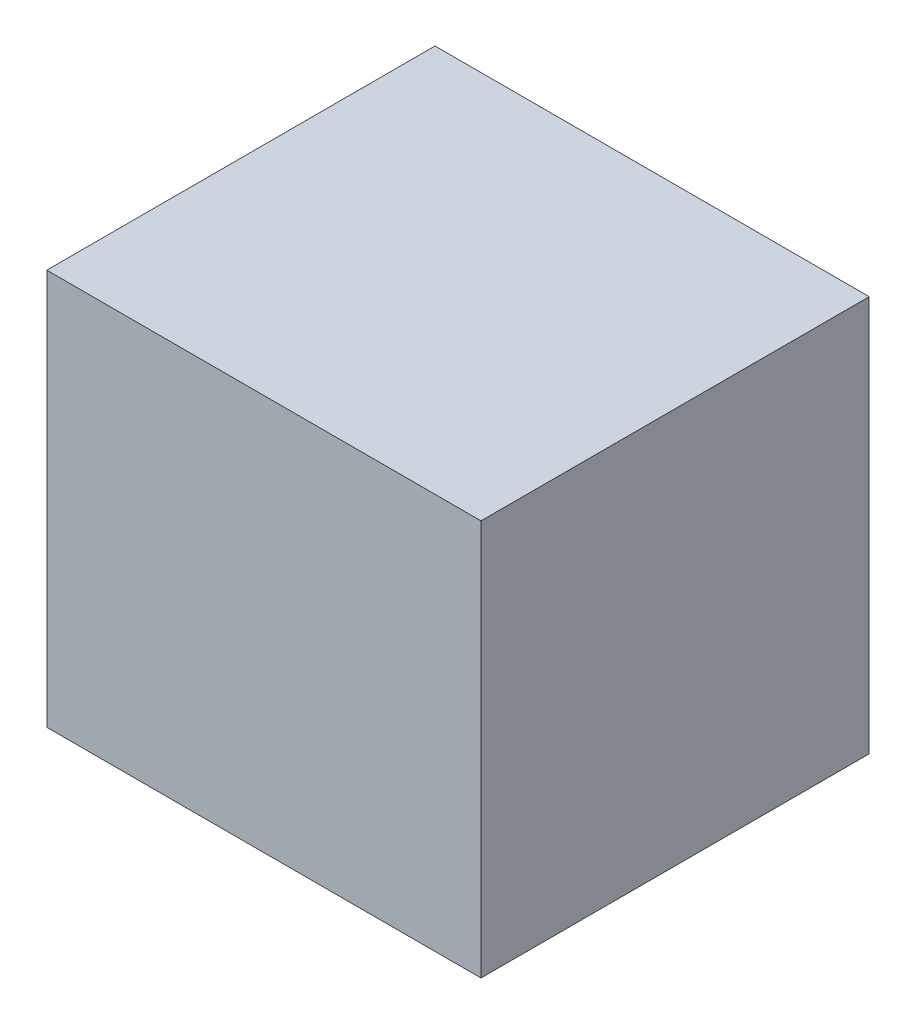
SolidWorks part; units mm, degrees
ref_plane "정면" through (0, 0, 0) normal (0, 0, 1) x (1, 0, 0)
ref_plane "윗면" through (0, 0, 0) normal (0, 1, 0) x (1, 0, 0)
ref_plane "우측면" through (0, 0, 0) normal (1, 0, 0) x (0, 0, -1)
sketch "Sketch1" plane through (0, 0, 0) normal (0, 0, 1) x (1, 0, 0)
  line L0 (42.5, -25) -> (42.5, 25) construction
  line L1 (27.5, 8.75) -> (44.5, 8.75)
  line L2 (27.5, 8.75) -> (27.5, -6.75)
  line L3 (27.5, -6.75) -> (44.5, -6.75)
  line L4 (44.5, 8.75) -> (44.5, -6.75)
  line L5 (27.5, 8.75) -> (44.5, -6.75) construction
  line L6 (27.5, -6.75) -> (44.5, 8.75) construction
  line L7 (-39.5, -28) -> (39.5, -28) construction
  point P0 (36, 1)
  dimension "D1" = 15.5
  dimension "D2" = 17
  dimension "D3" = 2
  dimension "D4" = 29
extrude "Boss-Extrude1" add sketch "Sketch1" along normal blind 15.2
